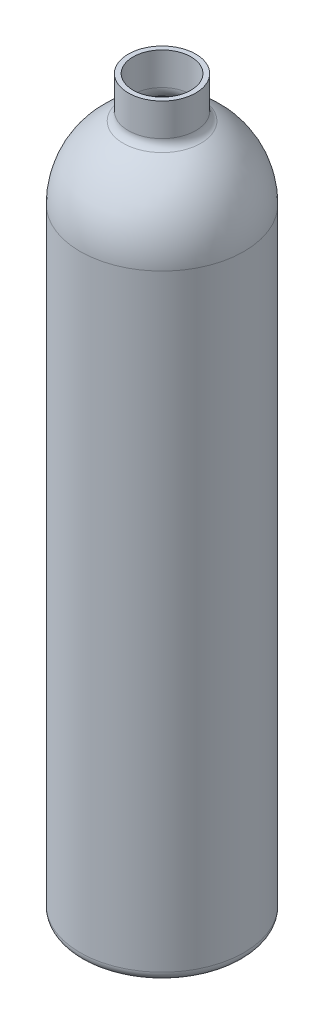
SolidWorks part; units mm, degrees
material "6061-T6 (SS)"
ref_plane "Front Plane" through (0, 0, 0) normal (0, 0, 1) x (1, 0, 0)
ref_plane "Top Plane" through (0, 0, 0) normal (0, 1, 0) x (1, 0, 0)
ref_plane "Right Plane" through (0, 0, 0) normal (1, 0, 0) x (0, 0, -1)
sketch "Sketch4" plane through (0, 0, 0) normal (1, 0, 0) x (0, 0, -1)
  line L1 (0, 0) -> (23.8125, 0)
  line L2 (0, 0) -> (0, 240.4934)
  line L4 (26.9875, 3.175) -> (26.9875, 203.2)
  line L5 (11.1125, 240.4934) -> (0, 240.4934)
  line L10 (11.1125, 240.4934) -> (11.1125, 229.764)
  arc A0 (26.9875, 203.2) -> (12.7836, 226.9677) centre (0, 203.2) ccw
  arc A1 (11.1125, 229.764) -> (12.7836, 226.9677) centre (14.2875, 229.764) ccw
  arc A2 (23.8125, 0) -> (26.9875, 3.175) centre (23.8125, 3.175) ccw
  point P10 (11.1125, 227.7934)
  point P11 (26.9875, 0)
  dimension "D8" = 3.175
  dimension "D3" = 3.175
  dimension "D1" = 26.9875
  dimension "D2" = 203.2
  dimension "D4" = 240.4934
  dimension "D5" = 11.1125
  dimension "D7" = 12.7
revolve "Revolve2" add sketch "Sketch4" angle 360 about L2
shell "Shell2" thickness 1.5875
